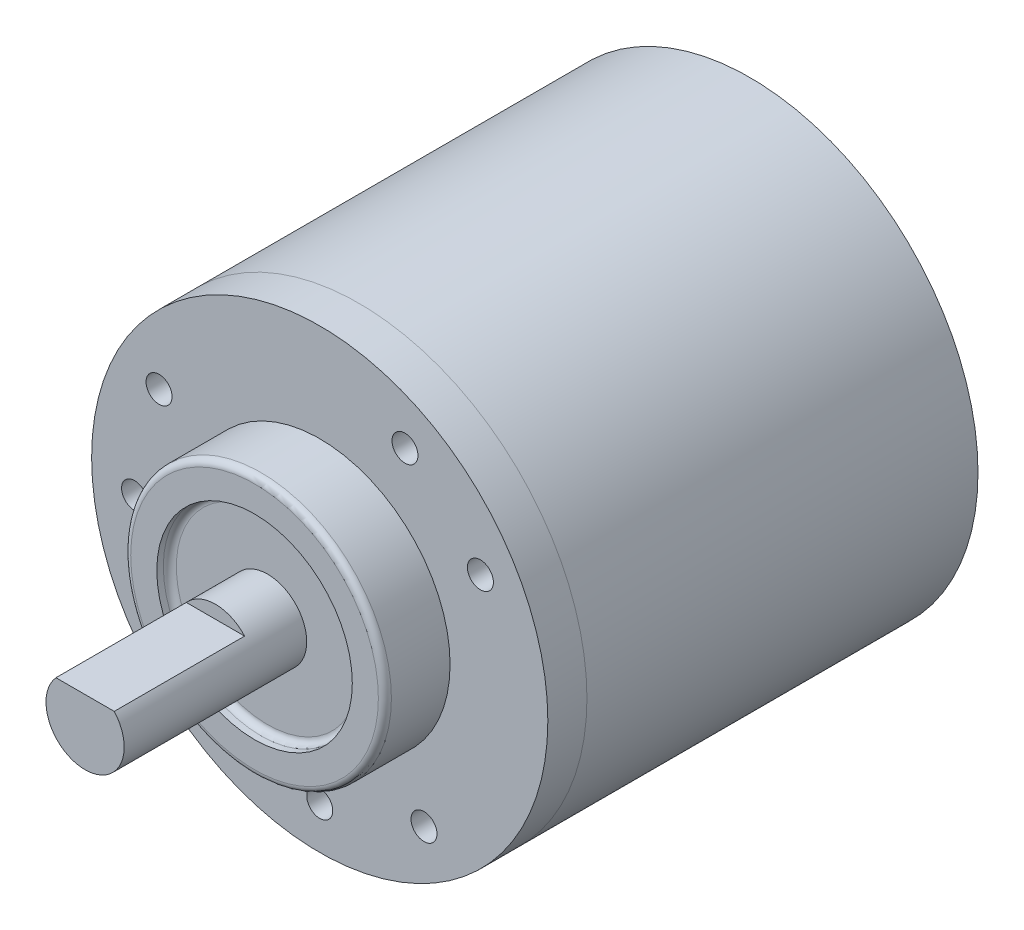
SolidWorks part; units mm, degrees
ref_plane "前视基准面" through (0, 0, 0) normal (0, 0, 1) x (1, 0, 0)
ref_plane "上视基准面" through (0, 0, 0) normal (0, 1, 0) x (1, 0, 0)
ref_plane "右视基准面" through (0, 0, 0) normal (1, 0, 0) x (0, 0, -1)
sketch "草图1" plane through (0, 0, 0) normal (0, 0, 1) x (1, 0, 0)
  circle A0 centre (0, 0) radius 17.5
  dimension "D1" = 35
extrude "凸台-拉伸2" add sketch "草图1" along normal blind 30
sketch "草图4" plane through (0, 0, 30) normal (0, 0, 1) x (1, 0, 0)
  circle A0 centre (0, 0) radius 17.5
  dimension "D1" = 35
extrude "凸台-拉伸4" add sketch "草图4" along normal blind 3 separate body
sketch "草图5" plane through (0, 0, 33) normal (0, 0, 1) x (1, 0, 0)
  circle A0 centre (0, 0) radius 10
  dimension "D1" = 20
extrude "凸台-拉伸5" add sketch "草图5" along normal blind 5
sketch "草图6" plane through (0, 0, 38) normal (0, 0, 1) x (1, 0, 0)
  circle A0 centre (0, 0) radius 7.5
  dimension "D1" = 15
extrude "切除-拉伸1" cut sketch "草图6" against normal blind 1
fillet "圆角1" radius 0.5 1 edges at (7.5, 0, 37)
sketch "草图7" plane through (0, 0, 37) normal (0, 0, 1) x (1, 0, 0)
  circle A0 centre (0, 0) radius 3
  dimension "D1" = 6
extrude "凸台-拉伸6" add sketch "草图7" along normal blind 4
sketch "草图8" plane through (0, 0, 41) normal (0, 0, 1) x (1, 0, 0)
  line L0 (-2.2361, 2) -> (2.2361, 2)
  arc A0 (-2.2361, 2) -> (2.2361, 2) centre (0, 0) ccw
  dimension "D1" = 2
  dimension "D2" = 3
extrude "凸台-拉伸7" add sketch "草图8" along normal blind 10
fillet "圆角2" radius 0.5 1 edges at (10, 0, 38)
ref_plane "基准面1" through (0, 17.5, 0) normal (0, 1, 0) x (1, 0, 0)
sketch "草图14" plane through (0, 0, 33) normal (0, 0, 1) x (1, 0, 0)
  line L0 (-12.3261, 7.1165) -> (0, -14.233) construction
  line L1 (0, -14.233) -> (12.3261, 7.1165) construction
  line L2 (12.3261, 7.1165) -> (-12.3261, 7.1165) construction
  circle A0 centre (0, 0) radius 14.233 construction
  dimension "D1" = 60
  dimension "D2" = 60
sketch "草图18" plane through (0, 0, 51) normal (0, 0, 1) x (1, 0, 0)
  line L0 (0, 0) -> (0, 19.7211) construction
  line L1 (0, 19.7211) -> (0, -20.299) construction
  line L2 (0, 0) -> (-23.5292, 0) construction
  line L3 (-23.5292, 0) -> (24.3495, 0) construction
sketch "草图20" plane through (0, 0, 33) normal (0, 0, 1) x (1, 0, 0)
  circle A0 centre (0, 0) radius 14.233 construction
  point P0 (22.9969, 13.6933)
  point P1 (6.5403, 12.6413)
  point P2 (-14.2055, -0.8835)
  point P5 (8, -11.7719)
  dimension "D1" = 8
  dimension "D2" = 8
  dimension "D3" = 8
hole_wizard "#3-48 螺纹孔1" positions "3D草图2" profile "草图21" tap size "#3-48" standard "ANSI Inch"
sketch3d "3D草图2"
  point P0 (0, -14.233, 33)
  point P3 (8, -11.7719, 33)
  point P6 (12.3261, 7.1165, 33)
  point P9 (6.5403, 12.6413, 33)
  point P12 (-12.3261, 7.1165, 33)
  point P15 (-14.2055, -0.8835, 33)
sketch "草图21" plane through (0, -14.233, 33) normal (1, 0, 0) x (0, -1, 0)
  line L0 (0, 0) -> (0, 13.239)
  line L1 (0, 13.239) -> (0.9969, 12.64)
  line L2 (0.9969, 12.64) -> (0.9969, 0)
  line L5 (0.9969, 0) -> (0, 0)
  line L10 (0, 13.239) -> (-0.9969, 12.64) construction
  line L11 (0, -6.35) -> (0, 107.95) construction
  dimension "螺纹孔钻头直径" = 1.9939
  dimension "螺纹孔钻头深度" = 12.64
  dimension "导头角度" = 118
cosmetic thread "孔螺蚊线1" parameters "D1"=10, "D2"=2.5146
cosmetic thread "孔螺蚊线2" parameters "D1"=10, "D2"=2.5146
cosmetic thread "孔螺蚊线3" parameters "D1"=10, "D2"=2.5146
cosmetic thread "孔螺蚊线4" parameters "D1"=10, "D2"=2.5146
cosmetic thread "孔螺蚊线5" parameters "D1"=10, "D2"=2.5146
cosmetic thread "孔螺蚊线6" parameters "D1"=10, "D2"=2.5146
